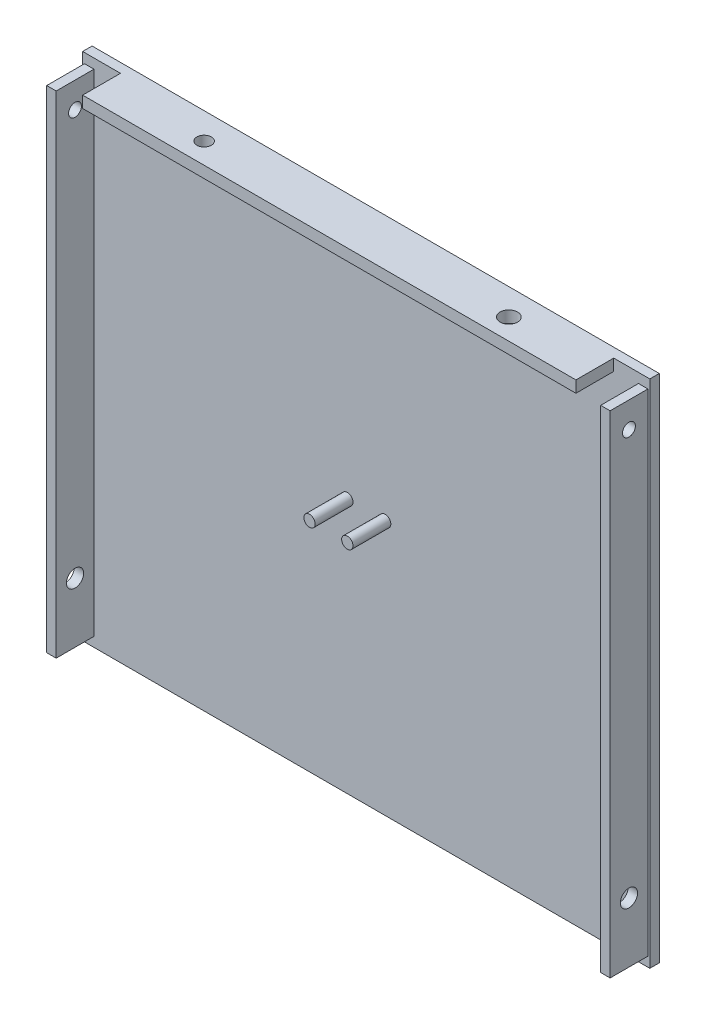
SolidWorks part; units mm, degrees
ref_plane "Alzado" through (0, 0, 0) normal (0, 0, 1) x (1, 0, 0)
ref_plane "Planta" through (0, 0, 0) normal (0, 1, 0) x (1, 0, 0)
ref_plane "Vista lateral" through (0, 0, 0) normal (1, 0, 0) x (0, 0, -1)
sketch "Croquis1" plane through (0, 0, 0) normal (0, 0, 1) x (1, 0, 0)
  line L1 (150, -135) -> (-150, -135)
  line L2 (150, -135) -> (150, 135)
  line L3 (150, 135) -> (-150, 135)
  line L4 (-150, -135) -> (-150, 135)
  line L5 (150, -135) -> (-150, 135) construction
  line L6 (150, 135) -> (-150, -135) construction
  point P0 (0, 0)
  dimension "D1" = 300
  dimension "D2" = 270
extrude "Saliente-Extruir1" add sketch "Croquis1" along normal blind 5
sketch "Croquis2" plane through (0, 0, 5) normal (0, 0, 1) x (1, 0, 0)
  line L0 (150, 135) -> (-150, 135) construction
  line L1 (-149, 129.8976) -> (-144, 129.8976)
  line L2 (-149, 129.8976) -> (-149, -129.929)
  line L3 (-149, -129.929) -> (-144, -129.929)
  line L4 (-144, 129.8976) -> (-144, -129.929)
  line L5 (149, 129.8976) -> (144, 129.8976)
  line L6 (149, 129.8976) -> (149, -129.929)
  line L7 (149, -129.929) -> (144, -129.929)
  line L8 (144, 129.8976) -> (144, -129.929)
  line L9 (-129.9827, 135) -> (130.9103, 135)
  line L10 (-129.9827, 135) -> (-129.9827, 128.8841)
  line L11 (-129.9827, 128.8841) -> (130.9103, 128.8841)
  line L12 (130.9103, 135) -> (130.9103, 128.8841)
  line L13 (-150, 135) -> (-150, -135) construction
  line L14 (150, -135) -> (150, 135) construction
  dimension "D1" = 5
  dimension "D2" = 5
  dimension "D3" = 1
  dimension "D4" = 1
extrude "Saliente-Extruir2" add sketch "Croquis2" along normal blind 20
sketch "Croquis3" plane through (-149, 0, 0) normal (-1, 0, 0) x (0, 0, 1)
  circle A0 centre (15.0362, 116.2977) radius 3.4177
  circle A1 centre (15.0362, -98.258) radius 4.5516
  point P4 (15.0362, -76.1912)
  point P5 (15.0362, -98.258)
extrude "Cortar-Extruir1" cut sketch "Croquis3" against normal through all
sketch "Croquis4" plane through (0, 0, 5) normal (0, 0, 1) x (1, 0, 0)
  circle A0 centre (-10, 0) radius 3
  circle A1 centre (10, 0) radius 3
  point P4 (-7.8673, 0)
  point P5 (6.4247, 0)
  point P6 (-6.6852, 0)
  dimension "D1" = 6
  dimension "D2" = 6
  dimension "D3" = 20
  dimension "D4" = 10
extrude "Saliente-Extruir3" add sketch "Croquis4" along normal blind 20
sketch "Croquis5" plane through (0, 135, 0) normal (0, 1, 0) x (1, 0, 0)
  circle A0 centre (-76.8099, -13.9433) radius 3.8418
  circle A1 centre (84.3762, -13.9433) radius 4.6282
extrude "Cortar-Extruir2" cut sketch "Croquis5" against normal blind 20
equation "\"D4@Croquis4\"=\"D3@Croquis4\"/2"
